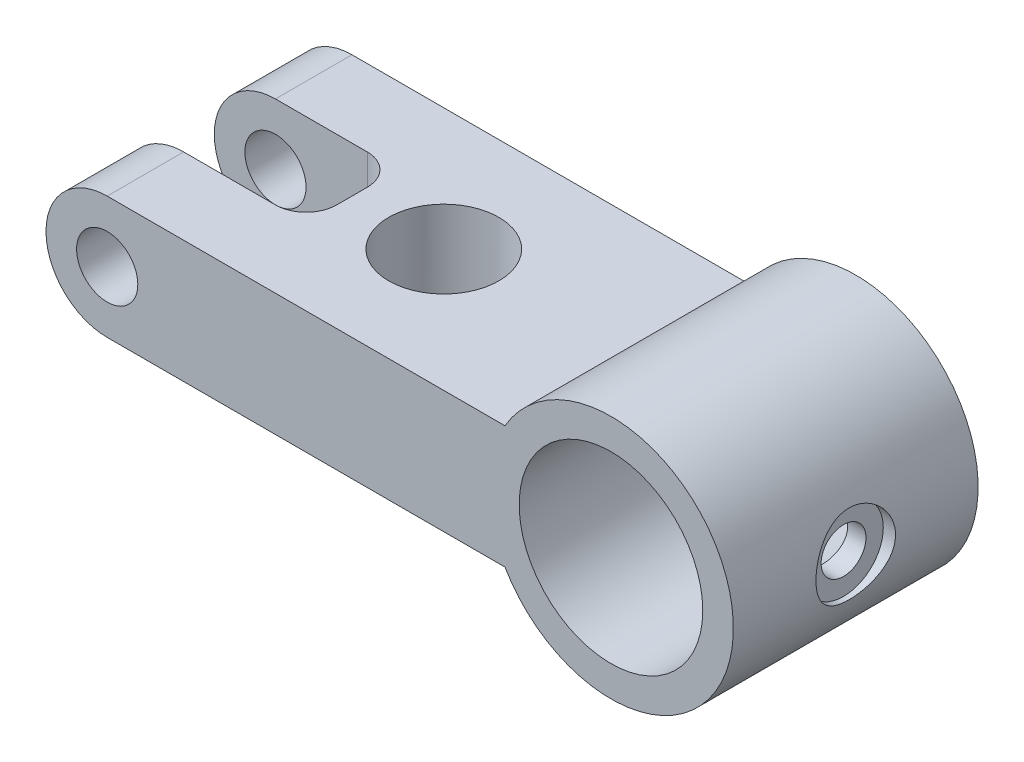
SolidWorks part; units mm, degrees
material "Alloy Steel (SS)"
ref_plane "Front Plane" through (0, 0, 0) normal (0, 0, 1) x (1, 0, 0)
ref_plane "Top Plane" through (0, 0, 0) normal (0, 1, 0) x (1, 0, 0)
ref_plane "Right Plane" through (0, 0, 0) normal (1, 0, 0) x (0, 0, -1)
other "Configuration Table"
sketch "Sketch1" plane through (0, 0, 0) normal (0, 0, 1) x (1, 0, 0)
  line L0 (-4.3994, 2.54) -> (-20.9094, 2.54)
  line L2 (-20.9094, -2.54) -> (-4.3994, -2.54)
  circle A0 centre (0, 0) radius 5.08
  arc A1 (-20.9094, 2.54) -> (-20.9094, -2.54) centre (-20.9094, 0) ccw
  circle A2 centre (-20.9094, 0) radius 1.27
  circle A3 centre (0, 0) radius 3.81
  dimension "D1" = 7.62
  dimension "D2" = 10.16
  dimension "D3" = 5.08
  dimension "D5" = 2.54
  dimension "D4" = 16.51
extrude "Boss-Extrude1" add sketch "Sketch1" along normal mid plane 10.16 contours A0 A3 | L0 A1 L2 A0
hole_wizard "#15 (0.18) Diameter Hole1" positions "Sketch3" profile "Sketch2" hole size "#15" standard "ANSI Inch" end condition through all
sketch "Sketch3" plane through (0, 2.54, 0) normal (0, 1, 0) x (1, 0, 0)
  line L0 (-23.4494, 5.08) -> (-23.4494, -5.08) construction
  point P0 (-12.0194, 0)
  dimension "D1" = 11.43
sketch "Sketch2" plane through (-12.0194, 2.54, 0) normal (1, 0, 0) x (0, 0, 1)
  line L0 (0, 0) -> (0, 7.62)
  line L1 (0, 7.62) -> (2.286, 7.62)
  line L2 (2.286, 7.62) -> (2.286, 0)
  line L5 (2.286, 0) -> (0, 0)
  line L11 (0, -6.35) -> (0, 107.95) construction
  dimension "Thru Hole Dia." = 4.572
  dimension "Thru Hole Depth" = 7.62
sketch "Sketch5" plane through (0, 2.54, 0) normal (0, 1, 0) x (1, 0, 0)
  line L0 (-23.4494, 5.08) -> (-23.4494, -5.08) construction
  line L1 (-31.0694, 1.905) -> (-15.8294, 1.905)
  line L2 (-31.0694, 1.905) -> (-31.0694, -1.905)
  line L3 (-31.0694, -1.905) -> (-15.8294, -1.905)
  line L4 (-15.8294, 1.905) -> (-15.8294, -1.905)
  line L5 (-31.0694, 1.905) -> (-15.8294, -1.905) construction
  line L6 (-31.0694, -1.905) -> (-15.8294, 1.905) construction
  point P0 (-23.4494, 0)
  point P7 (-15.8294, 0)
  dimension "D1" = 15.24
  dimension "D2" = 3.81
extrude "Cut-Extrude1" cut sketch "Sketch5" against normal up to surface (5.08 mm away) up to face at (-14.3054, -2.54, 0)
fillet "Fillet1" radius 1.27 2 edges at (-15.8294, 0, -1.905) (-15.8294, 0, 1.905)
sketch "Sketch8" plane through (0, 0, 0) normal (1, 0, 0) x (0, 0, -1)
  circle A0 centre (0, 0) radius 1.651
  dimension "D1" = 3.302
extrude "Cut-Extrude3" cut sketch "Sketch8" against normal blind 0.762 from offset 5.334
scale "Scale1" scale about centroid uniform scaling yes scale factor 1.5
sketch "Sketch7" plane through (0, 0, 0) normal (1, 0, 0) x (0, 0, -1)
  circle A0 centre (0, 0) radius 1.27
  dimension "D1" = 2.54
hole_wizard "#35 (0.11) Diameter Hole1" positions "Sketch10" profile "Sketch9" hole size "#35" standard "ANSI Inch"
sketch "Sketch10" plane through (11.0355, 0, 0) normal (1, 0, 0) x (0, 0, -1)
  point P0 (0, 0)
sketch "Sketch9" plane through (11.0355, 0, 0) normal (0, 1, 0) x (0, 0, -1)
  line L0 (0, 0) -> (0, 7.1894)
  line L1 (0, 7.1894) -> (1.397, 6.35)
  line L2 (1.397, 6.35) -> (1.397, 0)
  line L5 (1.397, 0) -> (0, 0)
  line L10 (0, 7.1894) -> (-1.397, 6.35) construction
  line L11 (0, -6.35) -> (0, 107.95) construction
  dimension "Hole Dia." = 2.794
  dimension "Hole Depth" = 6.35
  dimension "Drill Angle" = 118
